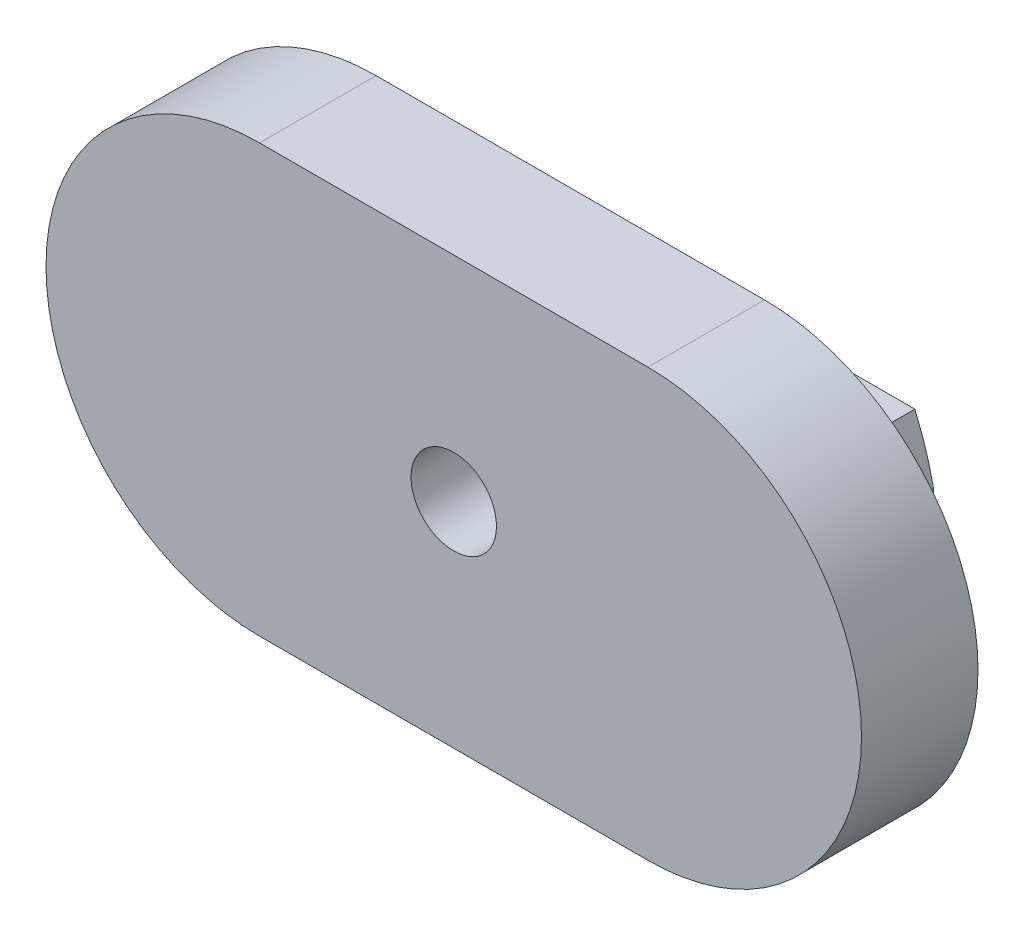
SolidWorks part; units mm, degrees
ref_plane "前视基准面" through (0, 0, 0) normal (0, 0, 1) x (1, 0, 0)
ref_plane "上视基准面" through (0, 0, 0) normal (0, 1, 0) x (1, 0, 0)
ref_plane "右视基准面" through (0, 0, 0) normal (1, 0, 0) x (0, 0, -1)
other "Configuration Table"
sketch "草图1" plane through (0, 0, 0) normal (0, 0, 1) x (1, 0, 0)
  line L0 (-5, 0) -> (5, 0) construction
  line L1 (-5, 5.5) -> (5, 5.5)
  line L2 (-5, -5.5) -> (5, -5.5)
  circle A0 centre (0, 0) radius 1.1
  arc A1 (-5, 5.5) -> (-5, -5.5) centre (-5, 0) ccw
  arc A2 (5, -5.5) -> (5, 5.5) centre (5, 0) ccw
  point P5 (0, 0)
  dimension "D1" = 2.2
  dimension "D2" = 11
  dimension "D3" = 10
extrude "凸台-拉伸1" add sketch "草图1" along normal blind 3
sketch "草图3" plane through (0, 0, 0) normal (0, 0, -1) x (-1, 0, 0)
  line L0 (-1.8028, 3) -> (-6.8739, 3)
  line L1 (-3.3541, 1) -> (-7.3541, 1)
  line L5 (-7.3541, 1.4721) -> (-7.3541, 1)
  line L6 (-7.3541, 0) -> (0, 0) construction
  line L7 (0, 0) -> (0, 5.5) construction
  line L8 (-5, 5.5) -> (5, 5.5) construction
  line L9 (-7.3541, -1.4721) -> (-7.3541, -1)
  line L10 (-3.3541, -1) -> (-7.3541, -1)
  line L11 (-1.8028, -3) -> (-6.8739, -3)
  line L12 (1.8028, -3) -> (6.8739, -3)
  line L13 (3.3541, -1) -> (7.3541, -1)
  line L14 (7.3541, -1.4721) -> (7.3541, -1)
  line L15 (7.3541, 1.4721) -> (7.3541, 1)
  line L16 (3.3541, 1) -> (7.3541, 1)
  line L17 (1.8028, 3) -> (6.8739, 3)
  arc A0 (-1.8028, 3) -> (-3.3541, 1) centre (0, 0) ccw
  arc A1 (-1.8028, -3) -> (-3.3541, -1) centre (0, 0) cw
  arc A2 (1.8028, -3) -> (3.3541, -1) centre (0, 0) ccw
  arc A3 (1.8028, 3) -> (3.3541, 1) centre (0, 0) cw
  arc A4 (-6.8739, 3) -> (-7.3541, 1.4721) centre (0, 0) ccw
  arc A5 (-7.3541, -1.4721) -> (-6.8739, -3) centre (0, 0) ccw
  arc A6 (6.8739, -3) -> (7.3541, -1.4721) centre (0, 0) ccw
  arc A7 (7.3541, 1.4721) -> (6.8739, 3) centre (0, 0) ccw
  dimension "D1" = 7
  dimension "D5" = 15
  dimension "D2" = 1
  dimension "D3" = 4
  dimension "D4" = 3
extrude "凸台-拉伸2" add sketch "草图3" along normal blind 2
